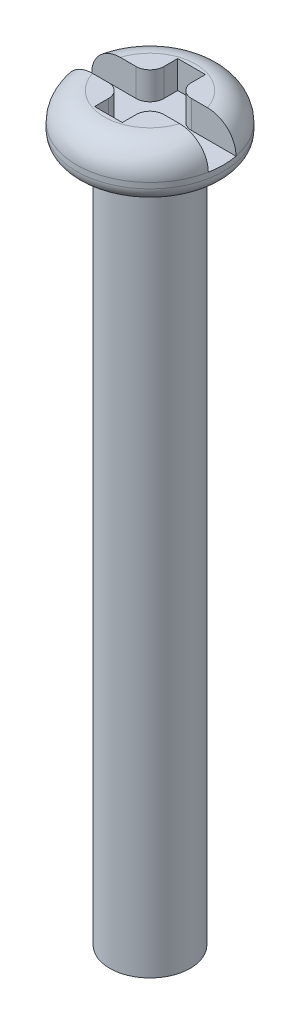
SolidWorks part; units mm, degrees
material "304不锈钢."
ref_plane "前视基准面" through (0, 0, 0) normal (0, 0, 1) x (1, 0, 0)
ref_plane "上视基准面" through (0, 0, 0) normal (0, 1, 0) x (1, 0, 0)
ref_plane "右视基准面" through (0, 0, 0) normal (1, 0, 0) x (0, 0, -1)
sketch "草图1" plane through (0, 0, 0) normal (0, 1, 0) x (1, 0, 0)
  circle A0 centre (0, 0) radius 1.45
  dimension "D1" = 2.9
extrude "凸台-拉伸1" add sketch "草图1" along normal blind 25
cosmetic thread "装饰螺纹线1" parameters "D1"=24.5, "D2"=2.013
sketch "草图2" plane through (0, 25, 0) normal (0, 1, 0) x (1, 0, 0)
  circle A0 centre (0, 0) radius 2.65
  dimension "D1" = 5.3
extrude "凸台-拉伸2" add sketch "草图2" along normal blind 1.7
sketch "草图3" plane through (0, 26.7, 0) normal (0, 1, 0) x (1, 0, 0)
  line L1 (-3, 0.5) -> (3, 0.5)
  line L2 (-3, 0.5) -> (-3, -0.5)
  line L3 (-3, -0.5) -> (3, -0.5)
  line L4 (3, 0.5) -> (3, -0.5)
  line L5 (-3, 0.5) -> (3, -0.5) construction
  line L6 (-3, -0.5) -> (3, 0.5) construction
  line L7 (-0.5, 1.5) -> (0.5, 1.5)
  line L8 (-0.5, 1.5) -> (-0.5, -1.5)
  line L9 (-0.5, -1.5) -> (0.5, -1.5)
  line L10 (0.5, 1.5) -> (0.5, -1.5)
  line L11 (-0.5, 1.5) -> (0.5, -1.5) construction
  line L12 (-0.5, -1.5) -> (0.5, 1.5) construction
  point P0 (0, 0)
  point P6 (0, 0)
  circle M9 centre (0, 0) radius 2.65
  dimension "D1" = 1
  dimension "D2" = 6
  dimension "D3" = 1
  dimension "D4" = 3
extrude "切除-拉伸1" cut sketch "草图3" against normal blind 1 contours L8 L1 L3 M9 | L10 L7 L8 L1 | L10 L1 L8 L3 | L10 L3 L8 L9 | L1 L10 L3 M9
fillet "圆角1" radius 0.5 4 edges at (0.5, 26.2, -0.5) (0.5, 26.2, 0.5) (-0.5, 26.2, -0.5) (-0.5, 26.2, 0.5)
fillet "圆角2" radius 1 2 edges at (0, 26.7, -2.65) (0, 26.7, 2.65)
fillet "圆角3" radius 0.5 1 edges at (0, 25, 2.65)
